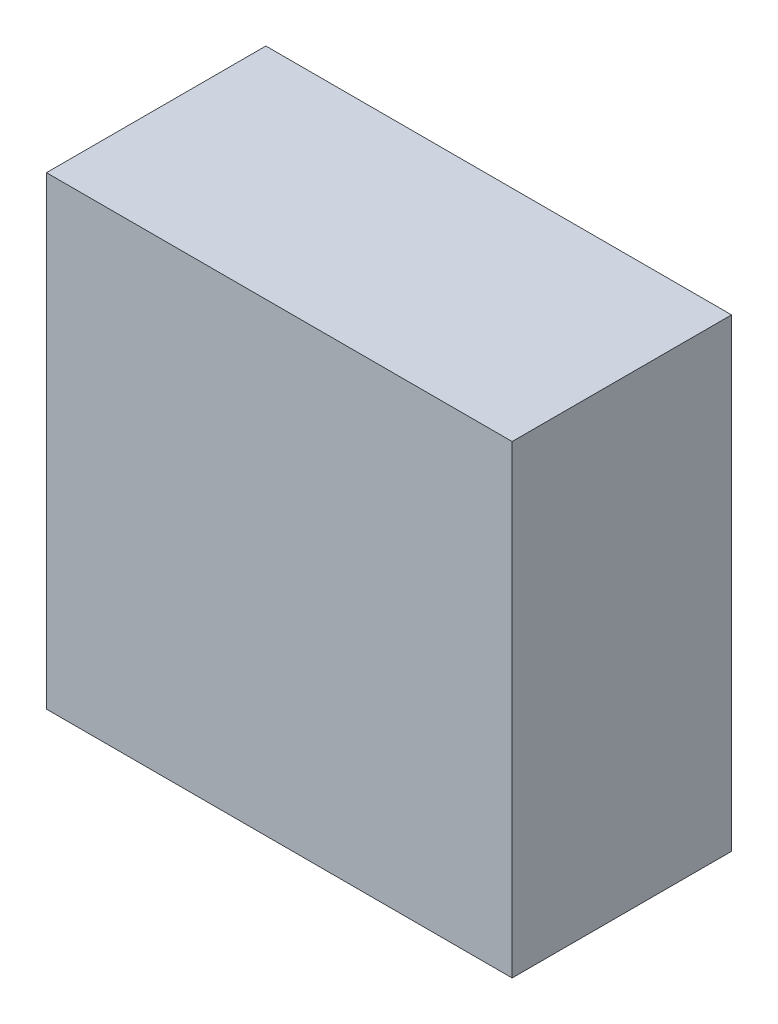
SolidWorks part; units mm, degrees
ref_plane "Front Plane" through (0, 0, 0) normal (0, 0, 1) x (1, 0, 0)
ref_plane "Top Plane" through (0, 0, 0) normal (0, 1, 0) x (1, 0, 0)
ref_plane "Right Plane" through (0, 0, 0) normal (1, 0, 0) x (0, 0, -1)
sketch "Sketch1" plane through (0, 0, 0) normal (0, 0, 1) x (1, 0, 0)
  line L0 (-1.1066, 1.016) -> (1.016, 1.016)
  line L1 (1.016, 1.016) -> (1.016, -1.1016)
  line L2 (1.016, -1.1016) -> (-1.1066, -1.1016)
  line L3 (-1.1066, -1.1016) -> (-1.1066, 1.016)
extrude "Component_Outline" add sketch "Sketch1" along normal blind 1 separate body
sketch3d "3DSketch1"
  line L0 (0, 0, 0) -> (1, 0, 0)
  line L1 (0, 0, 0) -> (0, 1, 0)
  line L2 (0, 0, 0) -> (0, 0, 1)
  point P0 (0, 0, 0)
